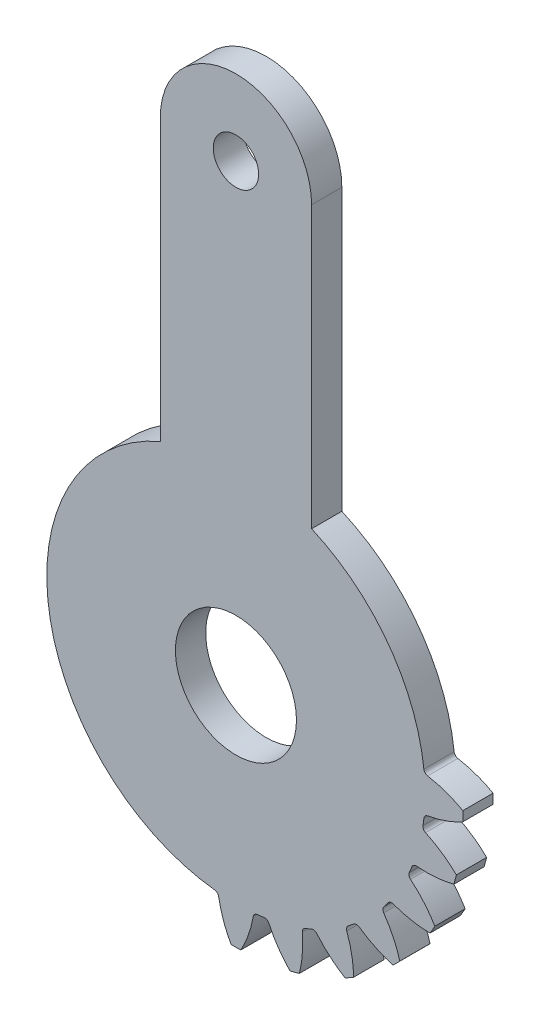
SolidWorks part; units mm, degrees
ref_plane "정면" through (0, 0, 0) normal (0, 0, 1) x (1, 0, 0)
ref_plane "윗면" through (0, 0, 0) normal (0, 1, 0) x (1, 0, 0)
ref_plane "우측면" through (0, 0, 0) normal (1, 0, 0) x (0, 0, -1)
sketch "스케치1" plane through (0, 0, 0) normal (0, 0, 1) x (1, 0, 0)
  line L1 (-5, 30) -> (-5, 11.4564)
  line L2 (5, 30) -> (5, 11.4564)
  arc A0 (-5, 11.4564) -> (5, 11.4564) centre (0, 0) ccw
  arc A1 (5, 30) -> (-5, 30) centre (0, 30) ccw
  circle A2 centre (0, 30) radius 1.5
  circle A3 centre (0, 0) radius 4
  circle A4 centre (0, 0) radius 14.5 construction
  circle A5 centre (0, 0) radius 17
  spline S0 degree 2 poles (-2.07, -12.3274) (-1.6343, -14.7617) (-0.57, -17) knots 0 0 0 1 1 1
  spline S1 degree 2 poles (2.07, -12.3274) (1.6343, -14.7617) (0.57, -17) knots 0 0 0 1 1 1
  dimension "D1" = 25
  dimension "D2" = 29
extrude "보스-돌출2" add sketch "스케치1" along normal blind 2 contours A5 L2 A1 L1 A2 | L2 A5 L1 A0 A3
sketch "스케치2" plane through (0, 0, 0) normal (0, 0, 1) x (1, 0, 0)
  line L1 (-5, 30) -> (-5, 11.4564)
  line L2 (5, 30) -> (5, 11.4564)
  arc A0 (-5, 11.4564) -> (5, 11.4564) centre (0, 0) ccw
  arc A1 (5, 30) -> (-5, 30) centre (0, 30) ccw
  circle A2 centre (0, 30) radius 1.5
  circle A3 centre (0, 0) radius 4
  circle A4 centre (0, 0) radius 13.75 construction
  circle A5 centre (0, 0) radius 15
  spline S0 degree 2 poles (-1.18, -12.4442) (-0.9848, -13.7988) (-0.32, -14.9966) knots 0 0 0 1 1 1
  spline S1 degree 2 poles (1.18, -12.4442) (0.9848, -13.7988) (0.32, -14.9966) knots 0 0 0 1 1 1
  dimension "D1" = 25
  dimension "D2" = 27.5
  dimension "D3" = 30
extrude "보스-돌출3" add sketch "스케치2" along normal blind 2 contours S1 A0 S0 A5
fillet "필렛1" radius 0.3 2 edges at (-1.18, -12.4442, 1) (1.18, -12.4442, 1)
pattern_circular "원형 패턴1" count 7 every 15 of "보스-돌출3", "필렛1"
